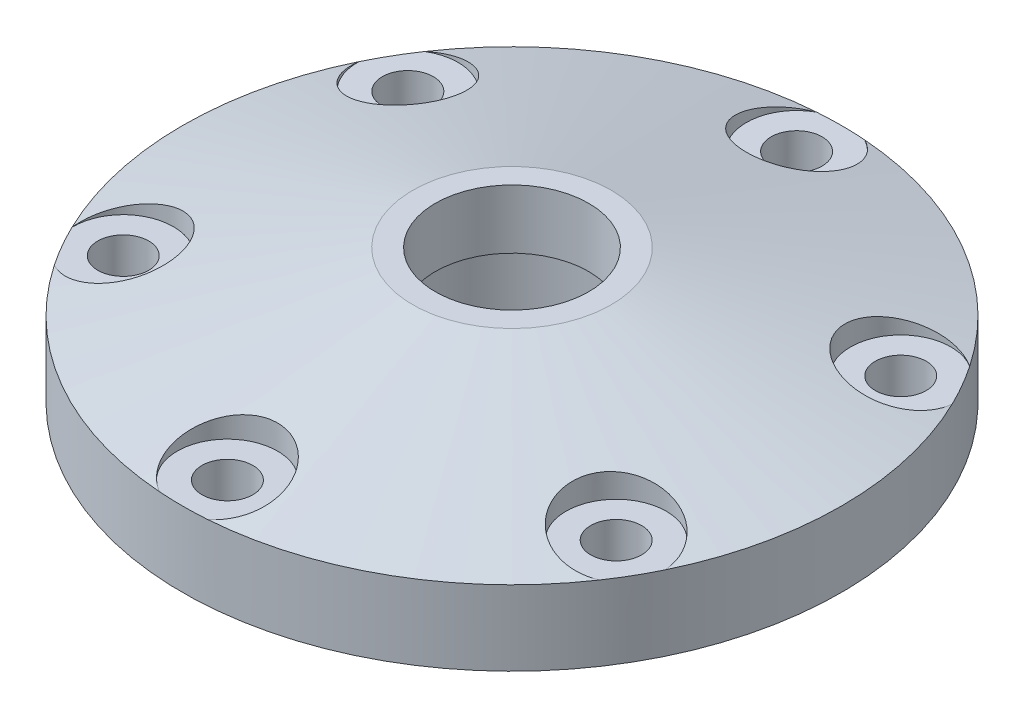
SolidWorks part; units mm, degrees
material "Hollow 3D Print"
ref_plane "Front Plane" through (0, 0, 0) normal (0, 0, 1) x (1, 0, 0)
ref_plane "Top Plane" through (0, 0, 0) normal (0, 1, 0) x (1, 0, 0)
ref_plane "Right Plane" through (0, 0, 0) normal (1, 0, 0) x (0, 0, -1)
sketch "Sketch1" plane through (0, 0, 0) normal (0, 0, 1) x (1, 0, 0)
  line L0 (0, 0) -> (0, 11.9562) construction
  line L1 (5.12, 5) -> (5.12, 8.9453)
  line L2 (5.12, 8.9453) -> (6.625, 8.9453)
  line L3 (6.625, 8.9453) -> (22, 5)
  line L6 (22, 5) -> (22, 0)
  line L7 (22, 0) -> (6.75, 0)
  line L8 (5.12, 5) -> (6.75, 5)
  line L9 (6.75, 5) -> (6.75, 0)
  dimension "D1" = 10.24
  dimension "D2" = 5
  dimension "D3" = 13.5
  dimension "D5" = 13.25
  dimension "D7" = 8.9453
  dimension "D8" = 5
  dimension "D9" = 44
revolve "Revolve1" add sketch "Sketch1" angle 360 about L0
ref_plane "Plane1" through (0, 5, 0) normal (0, 1, 0) x (1, 0, 0)
sketch "Sketch2" plane through (0, 5, 0) normal (0, 1, 0) x (1, 0, 0)
  point P0 (0, 19)
  point P4 (16.4545, 9.5)
  point P5 (16.4545, -9.5)
  point P6 (0, -19)
  point P7 (-16.4545, -9.5)
  point P8 (-16.4545, 9.5)
  point P9 (0, 0)
  dimension "D2" = 38
  dimension "D1" = 6
hole_wizard "M3 Clearance Hole1" positions "Sketch2" profile "Sketch3" hole size "M3" standard "ANSI Metric"
sketch "Sketch3" plane through (0, 5, -19) normal (1, 0, 0) x (0, 0, 1)
  line L0 (0, 0) -> (0, 6.0215)
  line L1 (0, 6.0215) -> (1.7, 5)
  line L2 (1.7, 5) -> (1.7, 0)
  line L5 (1.7, 0) -> (0, 0)
  line L10 (0, 6.0215) -> (-1.7, 5) construction
  line L11 (0, -6.35) -> (0, 107.95) construction
  dimension "Hole Dia." = 3.4
  dimension "Hole Depth" = 5
  dimension "Drill Angle" = 118
sketch "Sketch4" plane through (0, 5, 0) normal (0, 1, 0) x (1, 0, 0)
  circle A0 centre (-16.4545, 9.5) radius 1.7 construction
  circle A1 centre (0, 19) radius 1.7 construction
  circle A2 centre (16.4545, 9.5) radius 1.7 construction
  circle A3 centre (16.4545, -9.5) radius 1.7 construction
  circle A4 centre (0, -19) radius 1.7 construction
  circle A5 centre (-16.4545, -9.5) radius 1.7 construction
  circle A6 centre (-16.4545, 9.5) radius 1.7
  circle A7 centre (0, 19) radius 1.7
  circle A8 centre (16.4545, 9.5) radius 1.7
  circle A9 centre (16.4545, -9.5) radius 1.7
  circle A10 centre (0, -19) radius 1.7
  circle A11 centre (-16.4545, -9.5) radius 1.7
  point P0 (-16.4545, 9.5)
  point P2 (0, 19)
  point P4 (16.4545, 9.5)
  point P6 (16.4545, -9.5)
  point P8 (0, -19)
  point P10 (-16.4545, -9.5)
hole_wizard "CBORE for M3 SBHCS7" positions "Sketch4" profile "Sketch5" counterbore size "M3" standard "ANSI Metric"
sketch "Sketch5" plane through (-16.4545, 5, -9.5) normal (1, 0, 0) x (0, 0, -1)
  line L0 (0, 0) -> (0, 4.9668)
  line L1 (0, 4.9668) -> (1.7, 3.9453)
  line L2 (1.7, 3.9453) -> (1.7, 1.65)
  line L3 (1.7, 1.65) -> (3.35, 1.65)
  line L4 (3.35, 1.65) -> (3.35, 0)
  line L5 (3.35, 0) -> (0, 0)
  line L10 (0, 4.9668) -> (-1.7, 3.9453) construction
  line L11 (0, -6.35) -> (0, 107.95) construction
  dimension "Hole Dia." = 3.4
  dimension "Hole Depth" = 3.9453
  dimension "C'Bore Dia." = 6.7
  dimension "C'Bore Depth" = 1.65
  dimension "Drill Angle" = 118
